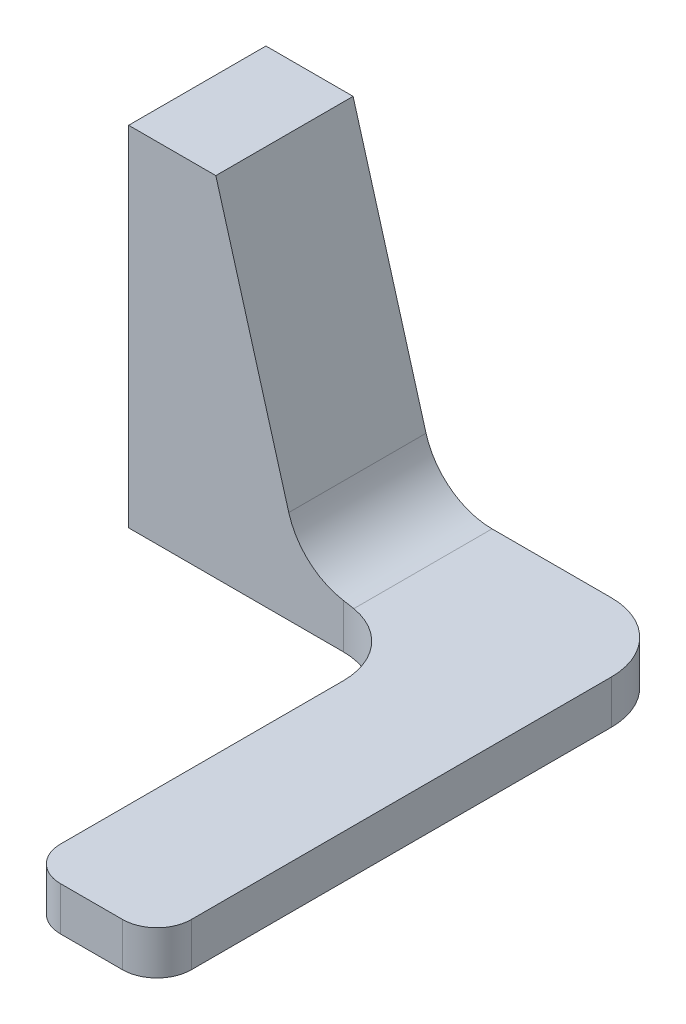
SolidWorks part; units mm, degrees
ref_plane "Front Plane" through (0, 0, 0) normal (0, 0, 1) x (1, 0, 0)
ref_plane "Top Plane" through (0, 0, 0) normal (0, 1, 0) x (1, 0, 0)
ref_plane "Right Plane" through (0, 0, 0) normal (1, 0, 0) x (0, 0, -1)
sketch "Sketch2" plane through (0, 0, 0) normal (0, 1, 0) x (1, 0, 0)
  line L0 (0, -10) -> (0, 10)
  line L5 (0, 10) -> (60.325, 10)
  line L6 (60.325, 10) -> (60.325, -66.2)
  line L7 (60.325, -66.2) -> (41.275, -66.2)
  line L8 (41.275, -66.2) -> (41.275, -10)
  line L9 (41.275, -10) -> (0, -10)
  line L10 (50.8, -66.2) -> (50.8, 10) construction
  dimension "D1" = 20
  dimension "D2" = 19.05
  dimension "D3" = 76.2
  dimension "D4" = 50.8
extrude "Boss-Extrude2" add sketch "Sketch2" along normal blind 50.8
sketch "Sketch3" plane through (0, 0, 0) normal (0, 0, 1) x (1, 0, 0)
  line L0 (0, 0) -> (0, 50.8) construction
  line L1 (0, 50.8) -> (12.7, 50.8) construction
  line L3 (0, 50.8) -> (41.275, 50.8) construction
  line L4 (12.7, 50.8) -> (25.4, 6.35)
  line L5 (25.4, 6.35) -> (60.325, 6.35)
  line L6 (60.325, 50.8) -> (60.325, 0) construction
  line L7 (60.325, 6.35) -> (60.325, 0) construction
  line L12 (60.325, 0) -> (0, 0) construction
  line L13 (12.7, 50.8) -> (60.325, 50.8)
  line L14 (60.325, 50.8) -> (60.325, 6.35)
  dimension "D1" = 6.35
  dimension "D2" = 12.7
  dimension "D3" = 12.7
extrude "Cut-Extrude1" cut sketch "Sketch3" against normal through all both and the other way through all
fillet "Fillet1" radius 10 1 edges at (25.4, 6.35, 0)
fillet "Fillet2" radius 10 2 edges at (60.325, 3.175, -10) (41.275, 3.175, 10)
fillet "Fillet3" radius 5 2 edges at (60.325, 3.175, 66.2) (41.275, 3.175, 66.2)
